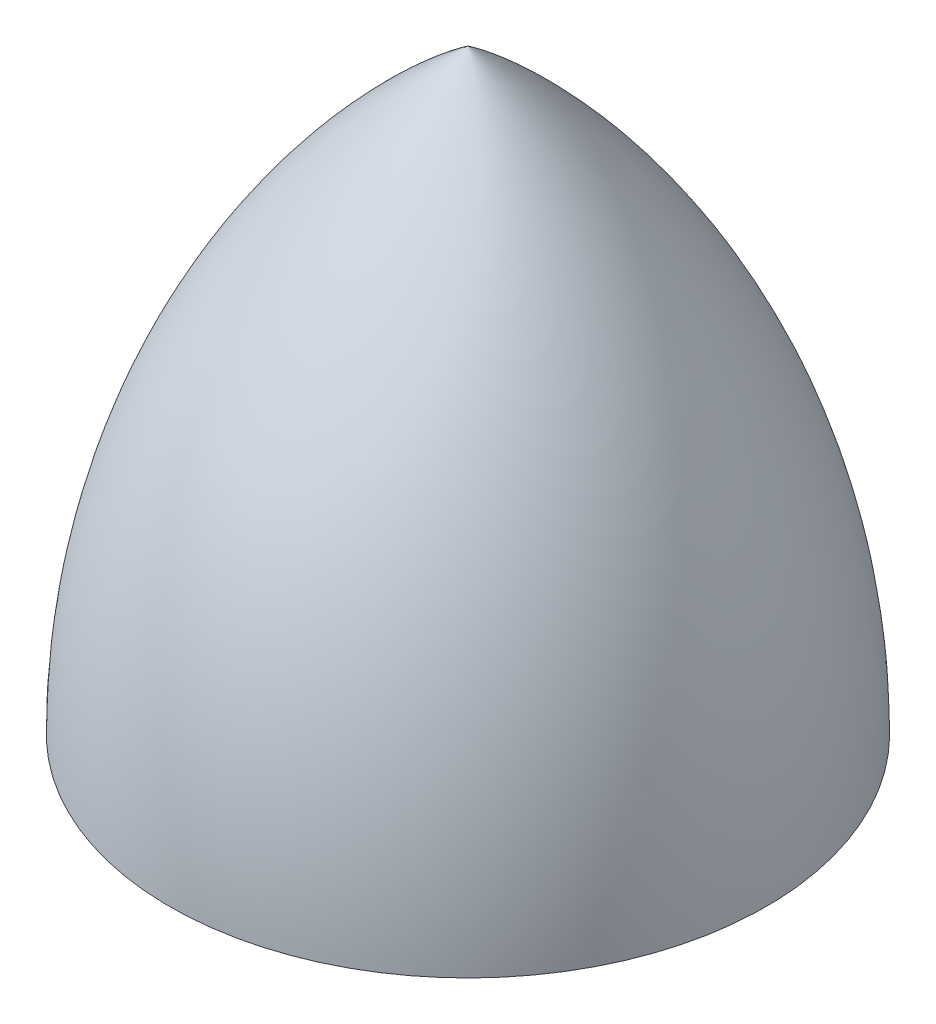
SolidWorks part; units mm, degrees
ref_plane "Front Plane" through (0, 0, 0) normal (0, 0, 1) x (1, 0, 0)
ref_plane "Top Plane" through (0, 0, 0) normal (0, 1, 0) x (1, 0, 0)
ref_plane "Right Plane" through (0, 0, 0) normal (1, 0, 0) x (0, 0, -1)
sketch "Sketch1" plane through (0, 0, 0) normal (0, 0, 1) x (1, 0, 0)
  line L0 (0, 30) -> (0, 0)
  line L1 (0, 0) -> (15, 0)
  arc A0 (15, 0) -> (0, 30) centre (-22.5, 0) ccw
  dimension "D1" = 15
  dimension "D2" = 30
revolve "Revolve1" add sketch "Sketch1" angle 360 about L0
